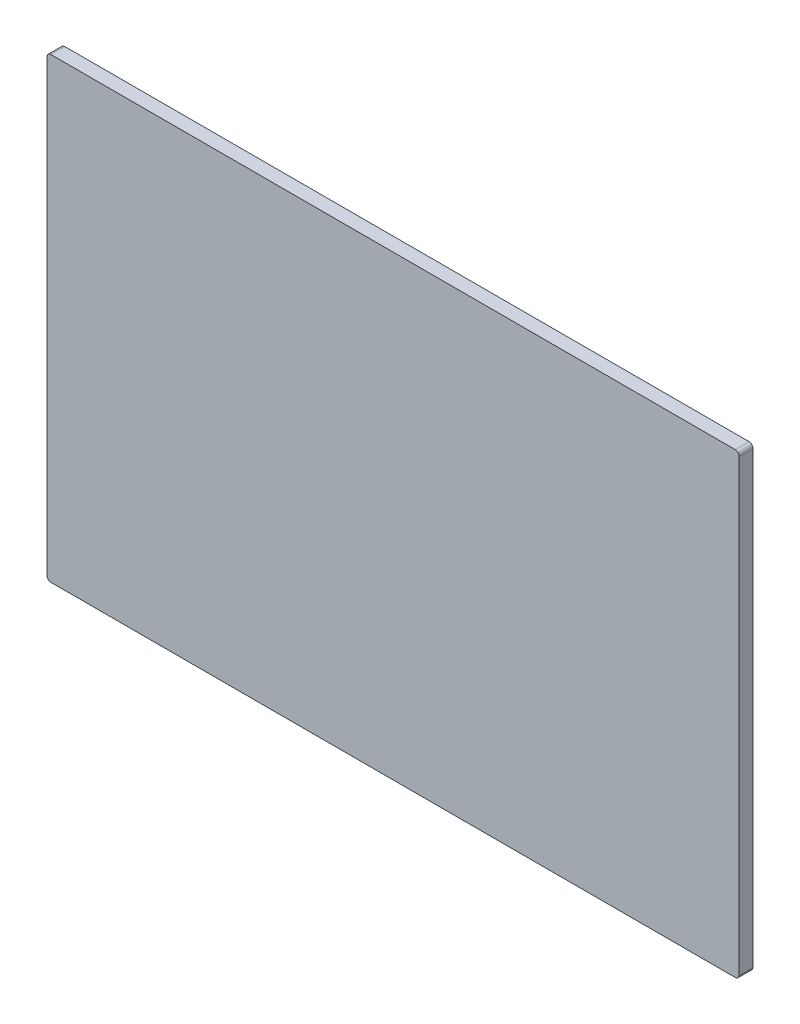
SolidWorks part; units mm, degrees
material "Copper"
ref_plane "Front Plane" through (0, 0, 0) normal (0, 0, 1) x (1, 0, 0)
ref_plane "Top Plane" through (0, 0, 0) normal (0, 1, 0) x (1, 0, 0)
ref_plane "Right Plane" through (0, 0, 0) normal (1, 0, 0) x (0, 0, -1)
sketch "Sketch1" plane through (0, 0, 0) normal (0, 0, 1) x (1, 0, 0)
  line L5 (95, 25.533) -> (965, 25.533)
  line L6 (95, 25.533) -> (95, 600.02)
  line L7 (95, 600.02) -> (965, 600.02)
  line L8 (965, 25.533) -> (965, 600.02)
extrude "Boss-Extrude1" add sketch "Sketch1" along normal blind 17.4
fillet "Fillet1" radius 5 1 edges at (965, 600.02, 8.7)
fillet "Fillet2" radius 5 1 edges at (95, 600.02, 8.7)
fillet "Fillet3" radius 5 1 edges at (95, 25.533, 8.7)
fillet "Fillet4" radius 5 1 edges at (965, 25.533, 8.7)
